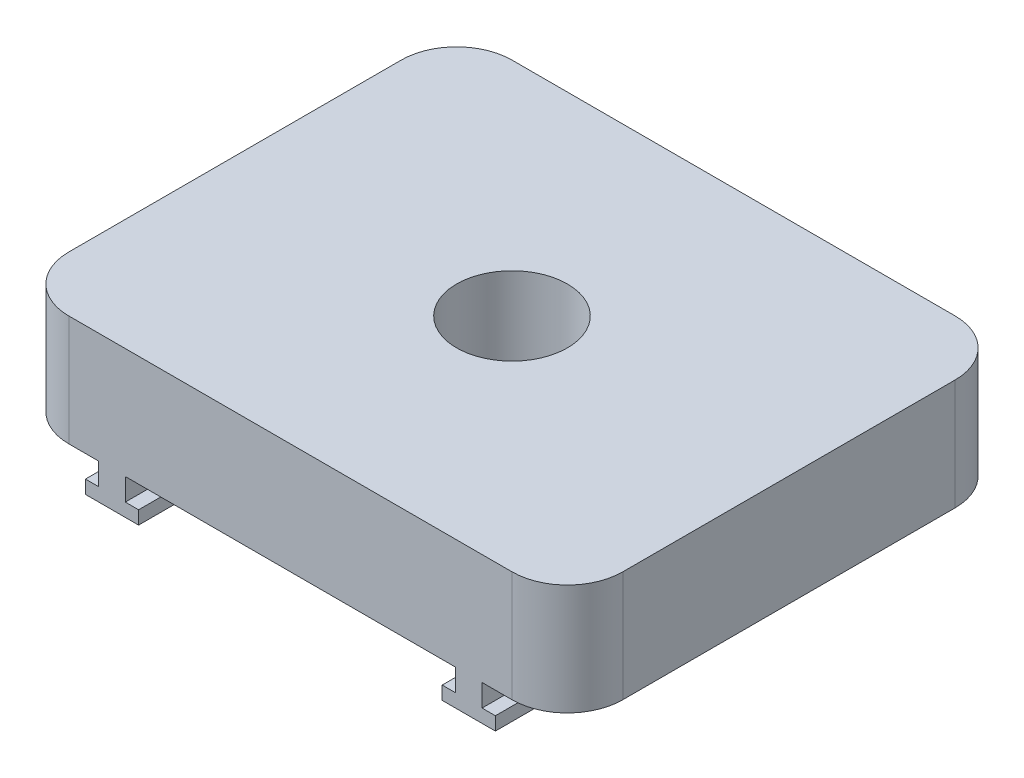
SolidWorks part; units mm, degrees
ref_plane "前视基准面" through (0, 0, 0) normal (0, 0, 1) x (1, 0, 0)
ref_plane "上视基准面" through (0, 0, 0) normal (0, 1, 0) x (1, 0, 0)
ref_plane "右视基准面" through (0, 0, 0) normal (1, 0, 0) x (0, 0, -1)
ref_plane "基准面4" through (0, -82, 0) normal (0, -1, 0) x (1, 0, 0)
sketch "草图1" plane through (0, -82, 0) normal (0, -1, 0) x (1, 0, 0)
  line L0 (-185, -200) -> (185, -200)
  line L1 (185, -200) -> (185, 200)
  line L2 (185, 200) -> (-185, 200)
  line L3 (-185, 200) -> (-185, -200)
extrude "凸台-拉伸1" add sketch "草图1" against normal blind 132
sketch "草图2" plane through (0, 0, 200) normal (0, 0, 1) x (1, 0, 0)
  line L0 (-185, -70) -> (-173, -70)
  line L1 (-173, -70) -> (-173, 50)
  line L2 (-173, 50) -> (-185, 50)
  line L3 (-185, 50) -> (-185, -70)
extrude "切除-拉伸1" cut sketch "草图2" against normal through all
sketch "草图3" plane through (-173, 0, 0) normal (-1, 0, 0) x (0, 0, 1)
  line L0 (-200, 50) -> (200, 50)
  line L1 (200, 50) -> (200, -50)
  line L2 (200, -50) -> (-200, -50)
  line L3 (-200, -50) -> (-200, 50)
extrude "凸台-拉伸2" add sketch "草图3" along normal blind 77
sketch "草图4" plane through (0, 0, 200) normal (0, 0, 1) x (1, 0, 0)
  line L0 (173, 50) -> (173, -70)
  line L1 (173, -70) -> (185, -70)
  line L2 (185, -70) -> (185, 50)
  line L3 (185, 50) -> (173, 50)
extrude "切除-拉伸2" cut sketch "草图4" against normal through all
sketch "草图5" plane through (173, 0, 0) normal (1, 0, 0) x (0, 0, -1)
  line L0 (200, -50) -> (-200, -50)
  line L1 (-200, -50) -> (-200, 50)
  line L2 (-200, 50) -> (200, 50)
  line L3 (200, 50) -> (200, -50)
extrude "凸台-拉伸3" add sketch "草图5" along normal blind 77
sketch "草图6" plane through (0, 0, -200) normal (0, 0, -1) x (-1, 0, 0)
  line L0 (-137, -82) -> (137, -82)
  line L1 (137, -82) -> (137, -70)
  line L2 (137, -70) -> (149, -70)
  line L3 (149, -70) -> (149, -50)
  line L4 (149, -50) -> (-149, -50)
  line L5 (-149, -50) -> (-149, -70)
  line L6 (-149, -70) -> (-137, -70)
  line L7 (-137, -70) -> (-137, -82)
extrude "切除-拉伸3" cut sketch "草图6" against normal through all
hole_wizard "孔1" positions "草图8" profile "草图7" legacy
sketch "草图8" plane through (0, -50, 0) normal (0, -1, 0) x (-1, 0, 0)
  point P0 (0, 0)
sketch "草图7" plane through (0, -50, 0) normal (1, 0, 0) x (0, 0, -1)
  line L0 (0, 0) -> (0, 100)
  line L1 (0, 100) -> (50, 100)
  line L2 (50, 100) -> (50, 0)
  line L3 (50, 0) -> (0, 0)
  line L4 (0, 110) -> (0, -10) construction
  dimension "直径" = 100
  dimension "深度" = 100
fillet "圆角1" radius 50 4 edges at (250, 0, -200) (-250, 0, -200) (250, 0, 200) (-250, 0, 200)
